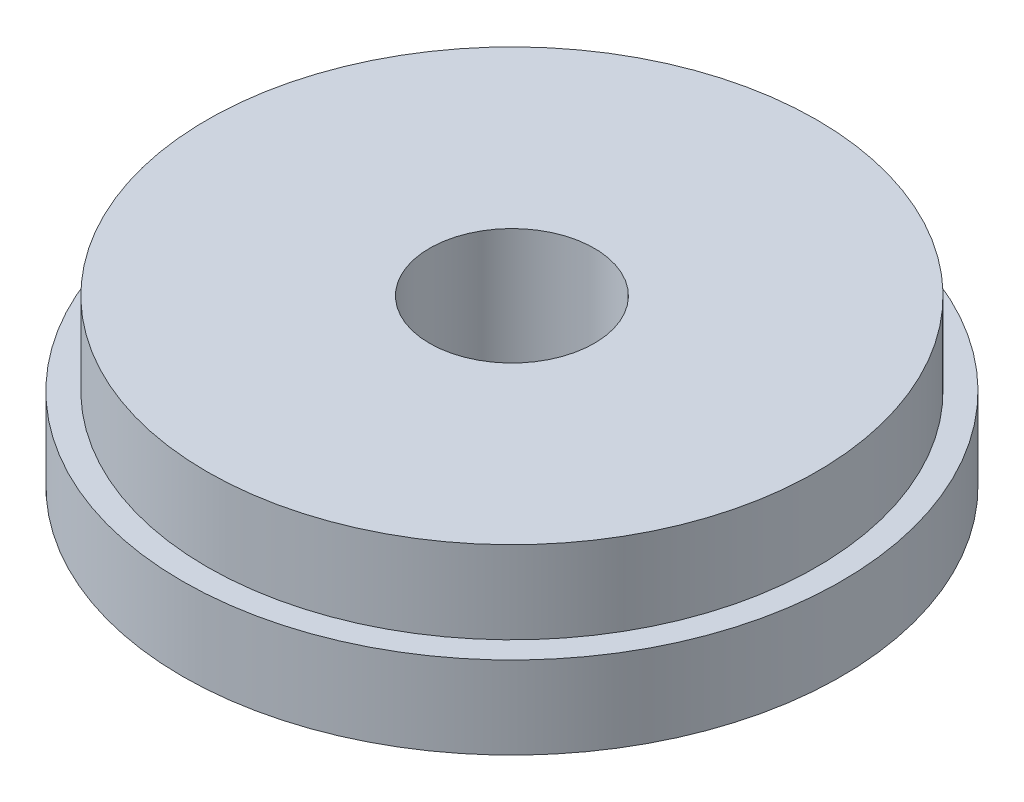
SolidWorks part; units mm, degrees
ref_plane "Front Plane" through (0, 0, 0) normal (0, 0, 1) x (1, 0, 0)
ref_plane "Top Plane" through (0, 0, 0) normal (0, 1, 0) x (1, 0, 0)
ref_plane "Right Plane" through (0, 0, 0) normal (1, 0, 0) x (0, 0, -1)
sketch "Sketch1" plane through (0, 0, 0) normal (0, 1, 0) x (1, 0, 0)
  circle A0 centre (0, 0) radius 20
  dimension "D1" = 40
extrude "Boss-Extrude1" add sketch "Sketch1" along normal blind 5 contours A0
sketch "Sketch2" plane through (0, 5, 0) normal (0, 1, 0) x (1, 0, 0)
  circle A0 centre (0, 0) radius 18.5
  dimension "D1" = 37
extrude "Boss-Extrude2" add sketch "Sketch2" along normal blind 5
sketch "Sketch3" plane through (0, 10, 0) normal (0, 1, 0) x (1, 0, 0)
  circle A0 centre (0, 0) radius 5
  dimension "D1" = 10
extrude "Cut-Extrude1" cut sketch "Sketch3" against normal through all
